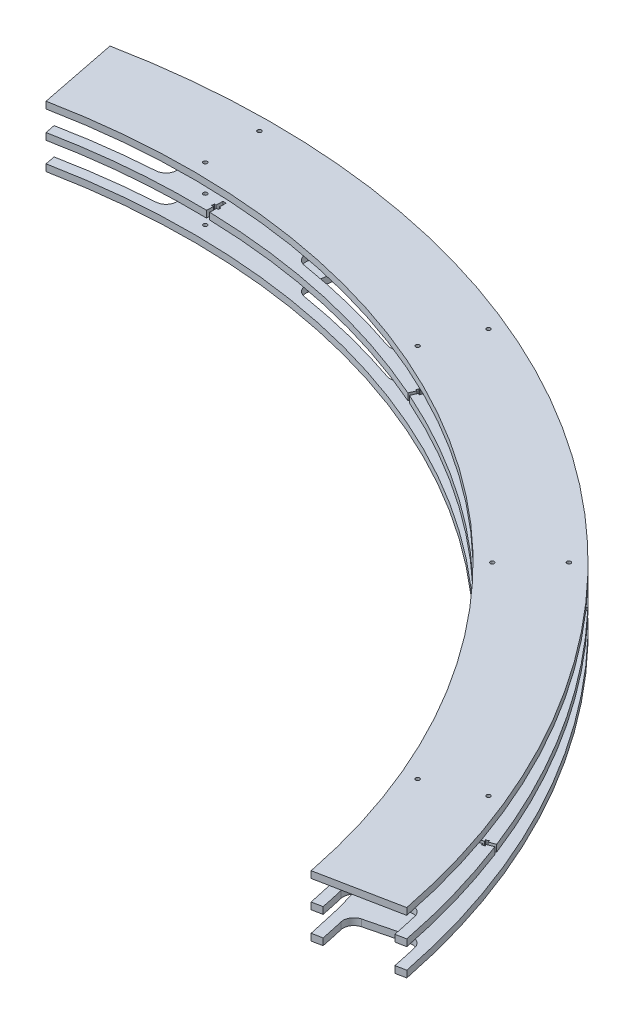
SolidWorks part; units mm, degrees
ref_plane "Front Plane" through (0, 0, 0) normal (0, 0, 1) x (1, 0, 0)
ref_plane "Top Plane" through (0, 0, 0) normal (0, 1, 0) x (1, 0, 0)
ref_plane "Right Plane" through (0, 0, 0) normal (1, 0, 0) x (0, 0, -1)
ref_plane "Plane1" through (0, -25.4, 0) normal (0, 1, 0) x (1, 0, 0)
ref_plane "Plane2" through (0, -50.8, 0) normal (0, 1, 0) x (1, 0, 0)
sketch "Sketch1" plane through (0, 0, 0) normal (0, 1, 0) x (1, 0, 0)
  circle A0 centre (0, 0) radius 636.6198
  circle A1 centre (0, 0) radius 712.8198
  dimension "D1" = 1273.2395
  dimension "D2" = 76.2
extrude "TrackTop" add sketch "Sketch1" along normal blind 6.35
sketch "Sketch11" plane through (0, -25.4, 0) normal (0, 1, 0) x (1, 0, 0)
  circle A0 centre (0, 0) radius 636.6198 construction
  circle A1 centre (0, 0) radius 636.6198
  circle A2 centre (0, 0) radius 712.8198 construction
  circle A3 centre (0, 0) radius 712.8198
extrude "Internal" add sketch "Sketch11" along normal blind 6.35 separate body
sketch "Sketch13" plane through (0, -50.8, 0) normal (0, 1, 0) x (1, 0, 0)
  circle A1 centre (0, 0) radius 636.6198 construction
  circle A2 centre (0, 0) radius 636.6198
  circle A3 centre (0, 0) radius 712.8198
  circle A5 centre (0, 0) radius 712.8198
  dimension "D1" = 0
extrude "TrackBottom" add sketch "Sketch13" along normal blind 6.35 separate body
sketch "Sketch6" plane through (0, 0, 0) normal (0, 1, 0) x (1, 0, 0)
  line L0 (636.6198, 0) -> (0, 0) construction
  line L1 (636.6198, 0) -> (649.3198, 0) construction
  line L2 (649.3198, 0) -> (700.1198, 0) construction
  line L3 (700.1198, 0) -> (712.8198, 0) construction
  circle A0 centre (649.3198, 0) radius 1.8288
  circle A1 centre (700.1198, 0) radius 1.8288
  circle A2 centre (0, 0) radius 636.6198 construction
  circle A3 centre (0, 0) radius 712.8198 construction
  dimension "D1" = 3.6576
  dimension "D2" = 12.7
sketch "Sketch8" plane through (0, 0, 0) normal (0, 0, 1) x (1, 0, 0)
  line L0 (0, 0) -> (0, 229.6647)
sketch "Sketch4" plane through (0, 0, 0) normal (0, 1, 0) x (1, 0, 0)
  line L0 (0, 0) -> (-203.1683, 1021.3961)
  line L1 (0, 0) -> (1021.3961, 203.1683)
  line L2 (-203.1683, 1021.3961) -> (-1224.5644, 818.2277)
  line L3 (-1224.5644, 818.2277) -> (-818.2277, -1224.5644)
  line L4 (-818.2277, -1224.5644) -> (1224.5644, -818.2277)
  line L5 (0, 0) -> (-1021.3961, -203.1683) construction
  line L6 (0, 0) -> (203.1683, -1021.3961) construction
  line L7 (1021.3961, 203.1683) -> (1224.5644, -818.2277)
  line L8 (0, 0) -> (0, 1252.6952) construction
  line L9 (0, 0) -> (545.1929, 815.9389) construction
  dimension "D1" = 90
  dimension "D2" = 11.25
  dimension "D3" = 45
extrude "MountingHoles" cut sketch "Sketch6" along normal through all both and the other way through all
pattern_circular "CirPattern3" count 16 over 360 about axis through (0, 0, 0) along (0, 1, 0) of "MountingHoles"
sketch "Sketch12" plane through (0, -25.4, 0) normal (0, 1, 0) x (1, 0, 0)
  line L0 (0, 0) -> (584.108, 276.2625) construction
  line L1 (626.6659, 296.3909) -> (593.079, 280.5055)
  line L2 (556.8017, 412.9522) -> (526.9592, 390.8196)
  line L3 (0, 0) -> (518.9883, 384.908) construction
  line L4 (0, 0) -> (1021.3961, 203.1683) construction
  line L5 (0, 0) -> (604.4884, 199.696) construction
  line L6 (604.4884, 199.696) -> (676.8425, 223.5985) construction
  arc A0 (579.8297, 285.1325) -> (524.7943, 376.9536) centre (0, 0) ccw
  arc A1 (631.3676, 309.8363) -> (570.8758, 410.7607) centre (0, 0) ccw
  circle A5 centre (0, 0) radius 712.8198 construction
  circle A6 centre (0, 0) radius 636.6198 construction
  arc A7 (579.8297, 285.1325) -> (593.079, 280.5055) centre (588.8034, 289.5453) ccw
  arc A8 (631.3676, 309.8363) -> (626.6659, 296.3909) centre (622.3903, 305.4308) cw
  arc A9 (524.7943, 376.9536) -> (526.9592, 390.8196) centre (532.9162, 382.7875) cw
  arc A10 (570.8758, 410.7607) -> (556.8017, 412.9522) centre (562.7586, 404.9202) ccw
  circle A11 centre (0, 0) radius 636.6198 construction
  circle A12 centre (640.6654, 211.6473) radius 20.6375
  circle A13 centre (0, 0) radius 712.8198 construction
  dimension "D5" = 10
  dimension "D6" = 41.275
  dimension "D3" = 11.25
  dimension "D4" = 14.063
  dimension "D2" = 9.525
  dimension "D1" = 9.525
  dimension "D7" = 7.031
extrude "Cutout" cut sketch "Sketch12" along normal blind 6.35 and the other way through all
pattern_circular "CirPattern4" count 16 over 360 about axis through (0, 0, 0) along (0, 1, 0) of "Cutout"
sketch "Sketch9" plane through (0, -25.4, 0) normal (0, 1, 0) x (1, 0, 0)
  line L1 (598.8318, 234.13) -> (599.336, 232.8229)
  line L6 (0, 0) -> (754.7575, 291.1421) construction
  line L7 (664.5057, 257.9616) -> (658.5812, 255.6763)
  line L8 (658.5812, 255.6763) -> (657.987, 257.2166) construction
  line L9 (657.987, 257.2166) -> (655.7653, 256.3596) construction
  line L10 (655.7653, 256.3596) -> (656.3595, 254.8193) construction
  line L11 (656.3595, 254.8193) -> (650.435, 252.5339)
  line L12 (650.435, 252.5339) -> (651.532, 249.6902)
  line L13 (651.532, 249.6902) -> (657.4565, 251.9755)
  line L14 (657.4565, 251.9755) -> (658.0507, 250.4351) construction
  line L15 (658.0507, 250.4351) -> (660.2724, 251.2921) construction
  line L16 (660.2724, 251.2921) -> (659.6782, 252.8325) construction
  line L17 (659.6782, 252.8325) -> (665.6027, 255.1178)
  line L18 (594.5084, 227.6938) -> (600.4329, 229.9791)
  line L19 (607.4822, 235.9652) -> (608.5791, 233.1214)
  line L20 (602.6546, 230.8361) -> (603.2488, 229.2957) construction
  line L21 (603.2488, 229.2957) -> (601.0271, 228.4387) construction
  line L22 (601.0271, 228.4387) -> (600.4329, 229.9791) construction
  line L23 (602.6546, 230.8361) -> (608.5791, 233.1214)
  line L24 (607.4822, 235.9652) -> (601.5577, 233.6799)
  line L25 (601.5577, 233.6799) -> (600.9635, 235.2202) construction
  line L26 (600.9635, 235.2202) -> (598.7418, 234.3632) construction
  line L27 (598.7418, 234.3632) -> (599.336, 232.8229) construction
  line L28 (599.336, 232.8229) -> (593.4115, 230.5375)
  line L30 (598.975, 234.4532) -> (600.7302, 235.1303)
  line L31 (601.0535, 234.987) -> (601.5577, 233.6799)
  line L32 (602.6546, 230.8361) -> (603.1588, 229.529)
  line L33 (603.0156, 229.2057) -> (601.2604, 228.5287)
  line L34 (600.9372, 228.672) -> (600.4329, 229.9791)
  line L35 (656.3595, 254.8193) -> (655.8553, 256.1264)
  line L36 (655.9986, 256.4496) -> (657.7538, 257.1267)
  line L37 (658.077, 256.9834) -> (658.5812, 255.6763)
  line L38 (659.6782, 252.8325) -> (660.1824, 251.5254)
  line L39 (660.0391, 251.2022) -> (658.2839, 250.5251)
  line L40 (657.9607, 250.6684) -> (657.4565, 251.9755)
  line L41 (0, 0) -> (1021.3961, 203.1683) construction
  arc A1 (598.8318, 234.13) -> (598.975, 234.4532) centre (598.7418, 234.3632) cw
  arc A7 (600.7302, 235.1303) -> (601.0535, 234.987) centre (600.9635, 235.2202) cw
  arc A8 (600.9372, 228.672) -> (601.2604, 228.5287) centre (601.0271, 228.4387) ccw
  arc A9 (603.0156, 229.2057) -> (603.1588, 229.529) centre (603.2488, 229.2957) ccw
  arc A10 (655.8553, 256.1264) -> (655.9986, 256.4496) centre (655.7653, 256.3596) cw
  arc A11 (657.7538, 257.1267) -> (658.077, 256.9834) centre (657.987, 257.2166) cw
  arc A12 (660.1824, 251.5254) -> (660.0391, 251.2022) centre (660.2724, 251.2921) cw
  arc A13 (658.2839, 250.5251) -> (657.9607, 250.6684) centre (658.0507, 250.4351) cw
  arc A14 (594.5084, 227.6938) -> (593.4115, 230.5375) centre (0, 0) ccw
  arc A15 (665.6027, 255.1178) -> (664.5057, 257.9616) centre (0, 0) ccw
  circle A16 centre (0, 0) radius 636.6198 construction
  circle A17 centre (0, 0) radius 712.8198 construction
  point P41 (665.0557, 256.5403)
  point P42 (593.9617, 229.1163)
  point P44 (608.0307, 234.5433)
  point P45 (650.9835, 251.112)
  point P50 (602.138, 228.8672)
  dimension "D6" = 0.25
  dimension "D1" = 2.3813
  dimension "D2" = 6.35
  dimension "D3" = 3.048
  dimension "D4" = 6.35
  dimension "D5" = 6.35
  dimension "D7" = 9.844
extrude "TeeNutSlots" cut sketch "Sketch9" along normal blind 6.35
pattern_circular "CirPattern5" count 16 over 360 about axis through (0, 0, 0) along (0, 1, 0) of "TeeNutSlots"
extrude "CutIntoQuarters" cut sketch "Sketch4" against normal through all both and the other way through all
sketch "Sketch5" plane through (0, 0, 0) normal (0, 1, 0) x (1, 0, 0)
  line L0 (-168.9992, 654.3223) -> (669.1882, 94.2634)
  line L1 (-168.9992, 654.3223) -> (-23.0722, 872.7174)
  line L2 (669.1882, 94.2634) -> (815.1151, 312.6585)
  line L3 (-23.0722, 872.7174) -> (815.1151, 312.6585)
  circle A0 centre (0, 0) radius 712.8198 construction
  dimension "D1" = 1008.0794
  dimension "D2" = 262.6616
equation "\"InternalCircumference\"= 4m"
equation "\"D1@Sketch1\"=\"InternalCircumference\"/PI"
equation "\"TrackWidth\"=76.2"
equation "\"D2@Sketch1\"=\"TrackWidth\""
equation "\"WallStudDiameter\"=6.35"
equation "\"D1@Sketch4\"=90"
equation "\"D2@Sketch4\"=360/32"
equation "\"SandwichBoltDiameter\"= 0.1440in'6-32"
equation "\"D1@Sketch6\"=\"SandwichBoltDiameter\""
equation "\"D7@Sketch9\"=360/256*7"
equation "\"D3@Sketch12\"=360/96*3"
equation "\"HoleEdgeSpacing\"= 1in / 2"
equation "\"D2@Sketch6\"=\"HoleEdgeSpacing\""
equation "\"TeeNutWidth\"= 6.35'4-40"
equation "\"D2@Sketch9\"=\"TeeNutWidth\""
equation "\"TeeNutHeight\"= 2.38125'4-40"
equation "\"D1@Sketch9\"=\"TeeNutHeight\""
equation "\"TeeNutDrillSize\"= 3.048'4-40"
equation "\"D3@Sketch9\"=\"TeeNutDrillSize\""
equation "\"HollowWallThickness\"=9.525"
equation "\"D2@Sketch12\"=\"HollowWallThickness\""
equation "\"D1@Sketch12\"=\"HollowWallThickness\""
equation "\"LegHoleDiameter\"= 13in / 8'1.25 in PVC"
equation "\"D6@Sketch12\"=\"LegHoleDiameter\""
equation "\"D4@Sketch12\"=360/128*5"
equation "\"D7@Sketch12\"=360/256*5"
